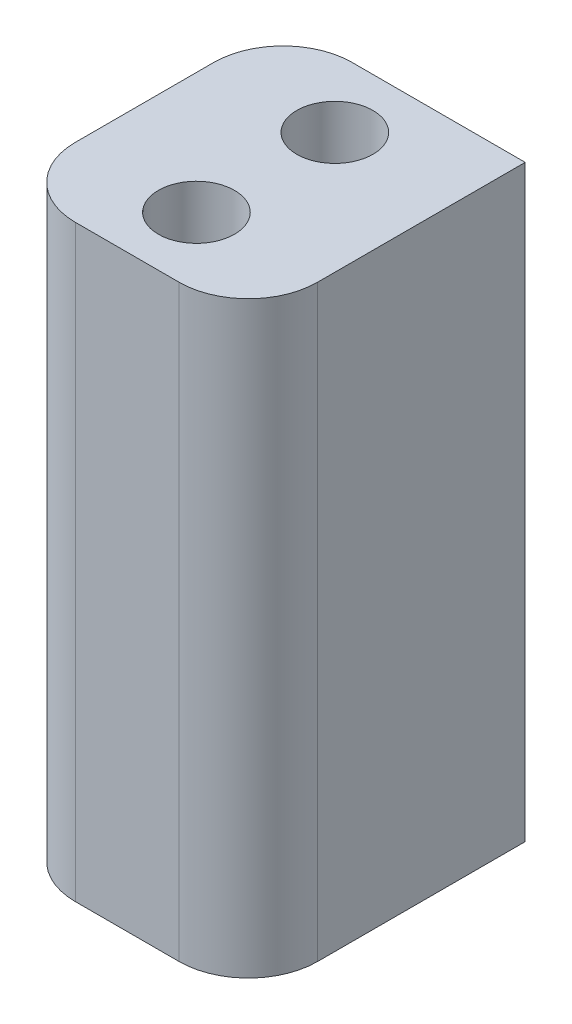
SolidWorks part; units mm, degrees
material "PLA"
ref_plane "前视基准面" through (0, 0, 0) normal (0, 0, 1) x (1, 0, 0)
ref_plane "上视基准面" through (0, 0, 0) normal (0, 1, 0) x (1, 0, 0)
ref_plane "右视基准面" through (0, 0, 0) normal (1, 0, 0) x (0, 0, -1)
sketch "草图1" plane through (0, 0, 0) normal (0, 1, 0) x (1, 0, 0)
  line L17 (7, 4) -> (7, -4)
  line L18 (0, -4) -> (7, -4)
  line L26 (0, -4) -> (0, 4)
  line L27 (0, 4) -> (7, 4)
  line L29 (3.5, 0) -> (3.5, 4) construction
  line L30 (0, 0) -> (7, 0) construction
  circle A1 centre (3.5, -2) radius 1.1
  circle A2 centre (3.5, 2) radius 1.1
  point P0 (0, 0)
  dimension "D4" = 7
  dimension "D1" = 2.2
  dimension "D2" = 8
  dimension "D3" = 2
extrude "凸台-拉伸1" add sketch "草图1" along normal blind 17
fillet "圆角1" radius 2 3 edges at (0, 8.5, 4) (0, 8.5, -4) (7, 8.5, 4)
